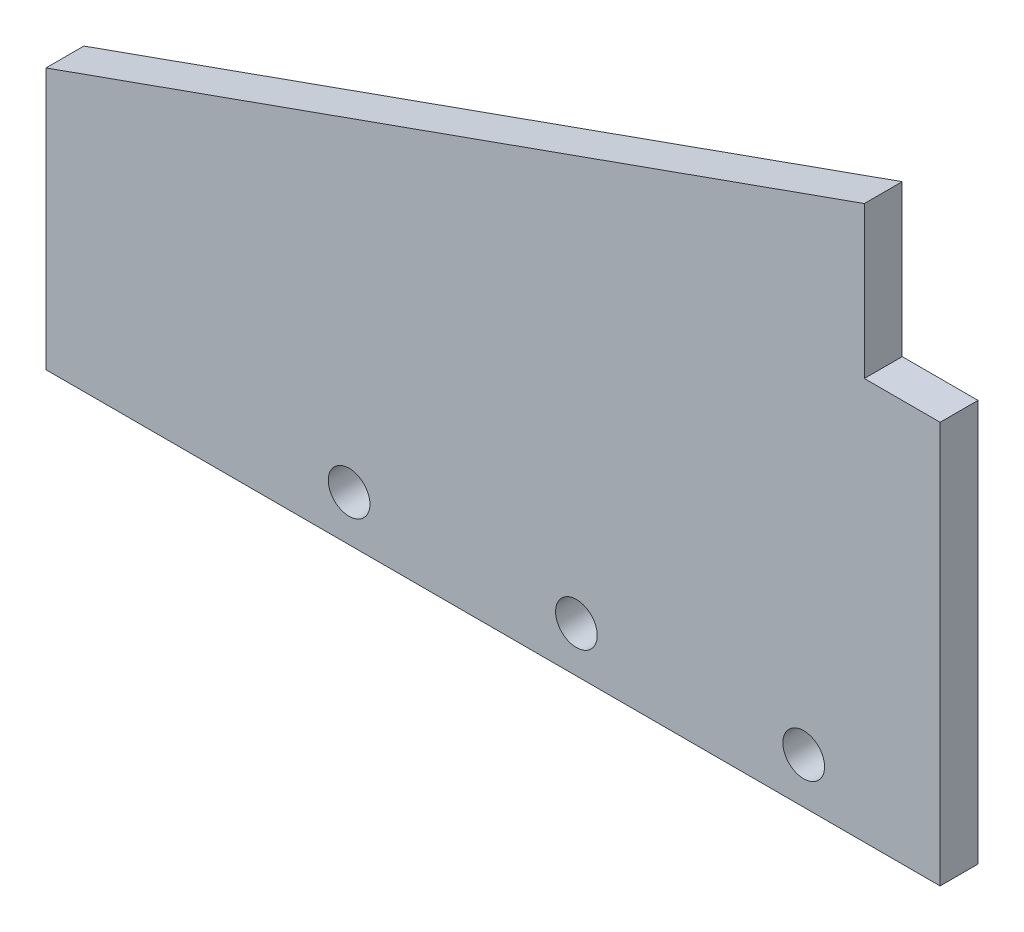
SolidWorks part; units mm, degrees
material "PVC 0.007 Plasticizado"
ref_plane "Plano frontal" through (0, 0, 0) normal (0, 0, 1) x (1, 0, 0)
ref_plane "Plano superior" through (0, 0, 0) normal (0, 1, 0) x (1, 0, 0)
ref_plane "Plano direito" through (0, 0, 0) normal (1, 0, 0) x (0, 0, -1)
sketch "Esboço1" plane through (0, 0, 0) normal (0, 0, 1) x (1, 0, 0)
  line L0 (0, 0) -> (0, 34.5)
  line L1 (0, 34.5) -> (108, 73)
  line L2 (118, 53) -> (118, 0)
  line L3 (118, 0) -> (0, 0)
  line L4 (118, 53) -> (108, 53)
  line L5 (108, 53) -> (108, 73)
  dimension "D1" = 34.5
  dimension "D2" = 20
  dimension "D3" = 118
  dimension "D4" = 10
  dimension "D5" = 73
extrude "Ressalto-extrusão1" add sketch "Esboço1" along normal blind 5
hole_wizard "Furo com folga de M51" positions "Esboço2" profile "Esboço3" hole size "M5" standard "ISO" end condition through all
sketch "Esboço2" plane through (0, 0, 5) normal (0, 0, 1) x (1, 0, 0)
  line L0 (118, 0) -> (118, 53) construction
  line L1 (0, 0) -> (118, 0) construction
  line L2 (118, 6) -> (0, 6) construction
  line L3 (0, 34.5) -> (0, 0) construction
  line L5 (5, 0) -> (5, 36.2824) construction
  line L6 (108, 73) -> (0, 34.5) construction
  point P0 (100, 6)
  point P2 (70, 6)
  point P4 (40, 6)
  dimension "D1" = 18
  dimension "D4" = 30
  dimension "D5" = 30
  dimension "D6" = 6
  dimension "D7" = 5
sketch "Esboço3" plane through (100, 6, 5) normal (1, 0, 0) x (0, -1, 0)
  line L0 (0, 0) -> (0, 5)
  line L1 (0, 5) -> (2.75, 5)
  line L2 (2.75, 5) -> (2.75, 0)
  line L5 (2.75, 0) -> (0, 0)
  line L11 (0, -6.35) -> (0, 107.95) construction
  dimension "Thru Hole Dia." = 5.5
  dimension "Thru Hole Depth" = 5
